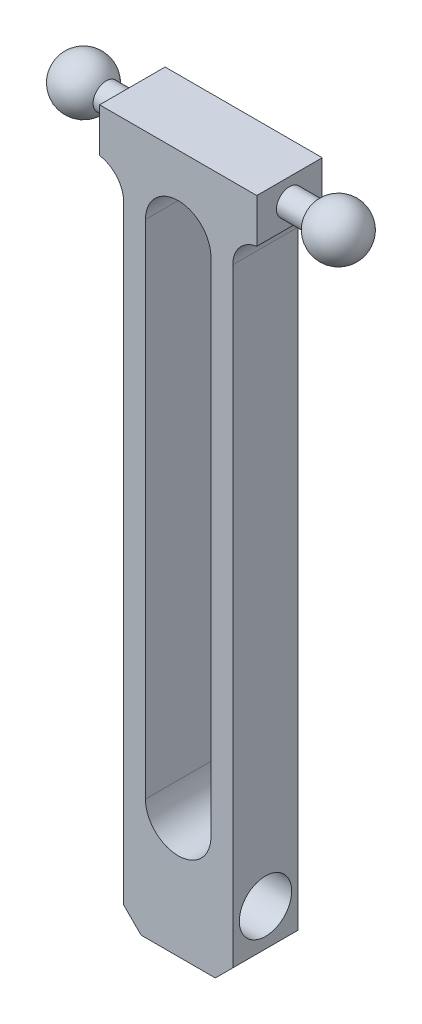
SolidWorks part; units mm, degrees
ref_plane "Ebene vorne" through (0, 0, 0) normal (0, 0, 1) x (1, 0, 0)
ref_plane "Ebene oben" through (0, 0, 0) normal (0, 1, 0) x (1, 0, 0)
ref_plane "Ebene rechts" through (0, 0, 0) normal (1, 0, 0) x (0, 0, -1)
sketch "Skizze1" plane through (0, 0, 0) normal (0, 0, 1) x (1, 0, 0)
  line L0 (-8.75, 75) -> (-3.25, 75)
  line L1 (2, 0) -> (10.5, 0)
  line L2 (0, 2) -> (0, 71.75)
  line L3 (15.75, 75) -> (21.25, 75)
  line L4 (12.5, 2) -> (12.5, 71.75)
  line L5 (-8.75, 75) -> (-8.75, 80)
  line L6 (10.5, 0) -> (12.5, 2)
  line L7 (-8.75, 80) -> (21.25, 80)
  line L8 (21.25, 80) -> (21.25, 75)
  line L9 (0, 2) -> (2, 0)
  arc A0 (15.75, 75) -> (12.5, 71.75) centre (15.75, 71.75) ccw
  arc A1 (-3.25, 75) -> (0, 71.75) centre (-3.25, 71.75) cw
  point P0 (0, 0)
  point P3 (12.5, 0)
  dimension "D5" = 3.25
  dimension "D1" = 12.5
  dimension "D2" = 30
  dimension "D3" = 8.75
  dimension "D4" = 5
  dimension "D7" = 5
  dimension "D8" = 80
extrude "Aufsatz-Linear austragen1" add sketch "Skizze1" along normal blind 7.5
sketch "Skizze2" plane through (0, 0, 7.5) normal (0, 0, 1) x (1, 0, 0)
  line L1 (6.25, 71.25) -> (6.25, 13.75) construction
  line L2 (10, 71.25) -> (10, 13.75)
  line L3 (2.5, 71.25) -> (2.5, 13.75)
  line L4 (0, 71.75) -> (0, 2) construction
  line L6 (15.75, 75) -> (21.25, 75) construction
  arc A0 (10, 71.25) -> (2.5, 71.25) centre (6.25, 71.25) ccw
  arc A1 (2.5, 13.75) -> (10, 13.75) centre (6.25, 13.75) ccw
  point P2 (6.25, 42.5)
  dimension "D3" = 7.5
  dimension "D1" = 6.25
  dimension "D2" = 57.5
extrude "Schnitt-Linear austragen1" cut sketch "Skizze2" against normal blind 10
sketch "Skizze7" plane through (12.5, 0, 0) normal (1, 0, 0) x (0, 0, -1)
  line L0 (-7.5, 0) -> (0, 0) construction
  line L1 (0, 2) -> (0, 71.75) construction
  circle A0 centre (-3.75, 6.25) radius 3
  dimension "D1" = 6
  dimension "D2" = 6.25
  dimension "D3" = 3.75
extrude "Schnitt-Linear austragen4" cut sketch "Skizze7" against normal through all
hole_wizard "M4 Gewindebohrung1" positions "3D-Skizze2" profile "Skizze8" tap size "M4" standard "DIN"
sketch3d "3D-Skizze2"
  line L0 (12.5, 0, 7.5) -> (12.5, 0, 0) construction
  line L1 (2, 0, 7.5) -> (10.5, 0, 7.5) construction
  point P2 (6.25, 0, 3.75)
  dimension "D2" = 6.25
  dimension "D3" = 3.75
sketch "Skizze8" plane through (6.25, 0, 3.75) normal (1, 0, 0) x (0, 0, -1)
  line L0 (0, 0) -> (0, 8.4914)
  line L1 (0, 8.4914) -> (1.65, 7.5)
  line L2 (1.65, 7.5) -> (1.65, 0)
  line L5 (1.65, 0) -> (0, 0)
  line L10 (0, 8.4914) -> (-1.65, 7.5) construction
  line L11 (0, -6.35) -> (0, 107.95) construction
  dimension "Bohrerdurchmesser" = 3.3
  dimension "Bohrungstiefe" = 7.5
  dimension "Spitzenwinkel" = 118
cosmetic thread "Bohrungsgewinde1" parameters "D1"=4.3718, "D2"=4
sketch "Skizze9" plane through (21.25, 0, 0) normal (1, 0, 0) x (0, 0, -1)
  line L0 (-7.5, 80) -> (0, 80) construction
  line L1 (-7.5, 75) -> (-7.5, 80) construction
  circle A0 centre (-3.75, 77.5) radius 1.5
  dimension "D1" = 3
  dimension "D2" = 2.5
  dimension "D3" = 3.75
extrude "Schnitt-Linear austragen5" cut sketch "Skizze9" against normal blind 6 flip side to cut
sketch "Skizze10" plane through (-8.75, 0, 0) normal (-1, 0, 0) x (0, 0, 1)
  circle A0 centre (3.75, 77.5) radius 1.5
  circle A1 centre (3.75, 77.5) radius 1.5 construction
  dimension "D1" = 3
extrude "Schnitt-Linear austragen6" cut sketch "Skizze10" against normal blind 6 flip side to cut
ref_plane "Ebene1" through (0, 77.5, 0) normal (0, 1, 0) x (1, 0, 0)
sketch "Skizze11" plane through (0, 77.5, 0) normal (0, 1, 0) x (1, 0, 0)
  line L0 (18.25, -2.25) -> (18.25, -3.75)
  line L5 (-5.75, -2.25) -> (-5.75, -3.75)
  line L6 (-8.75, -2.25) -> (-8.75, -5.25) construction
  line L7 (-8.75, -3.75) -> (21.25, -3.75) construction
  line L8 (21.25, -5.25) -> (21.25, -2.25) construction
  line L9 (-2.75, -7.5) -> (-2.75, 0) construction
  line L11 (-5.75, -3.75) -> (-11.3481, -3.75)
  line L12 (18.25, -3.75) -> (23.8481, -3.75)
  arc A0 (-5.75, -2.25) -> (-11.3481, -3.75) centre (-8.3481, -3.75) ccw
  arc A1 (23.8481, -3.75) -> (18.25, -2.25) centre (20.8481, -3.75) ccw
  dimension "D3" = 24
  dimension "D2" = 3
  dimension "D4" = 3
revolve "Rotation2" add sketch "Skizze11" angle 360 about L7
